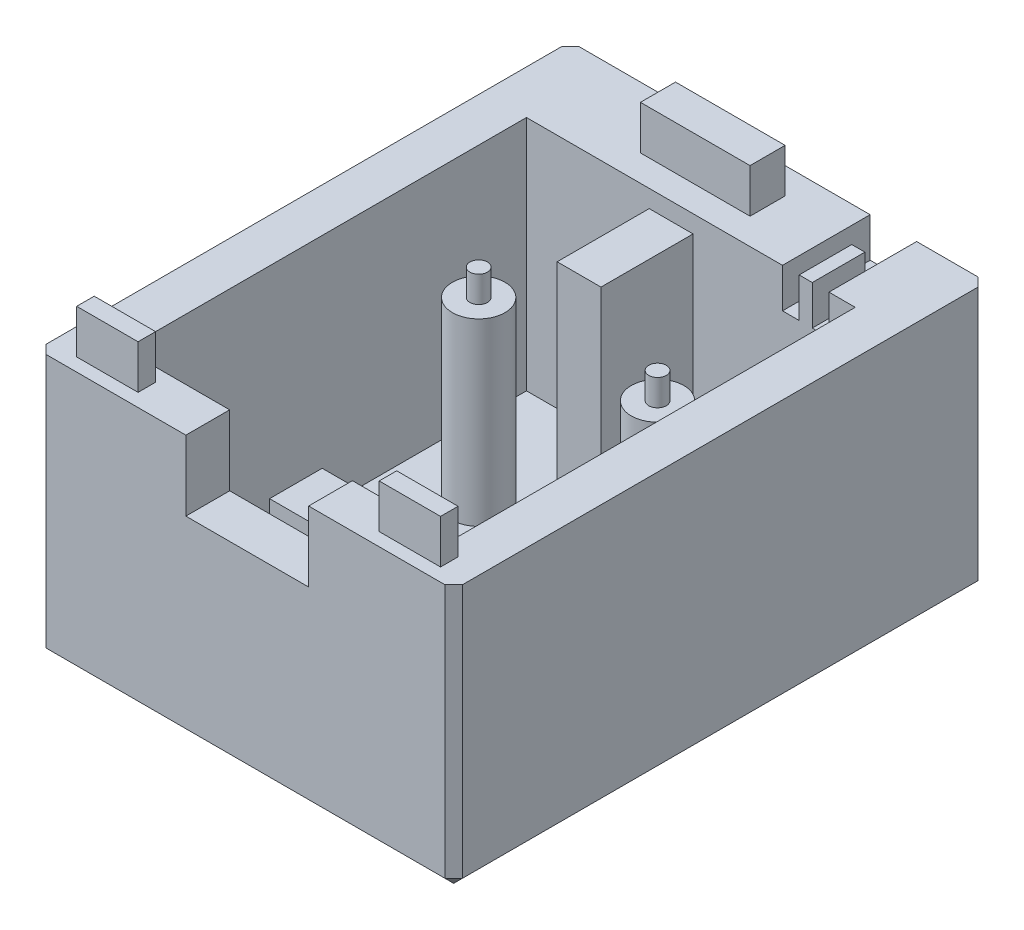
SolidWorks part; units mm, degrees
ref_plane "前视基准面" through (0, 0, 0) normal (0, 0, 1) x (1, 0, 0)
ref_plane "上视基准面" through (0, 0, 0) normal (0, 1, 0) x (1, 0, 0)
ref_plane "右视基准面" through (0, 0, 0) normal (1, 0, 0) x (0, 0, -1)
other "Configuration Table"
sketch "草图1" plane through (0, 0, 0) normal (0, 1, 0) x (1, 0, 0)
  line L1 (-50.0333, 28.8167) -> (-2.5333, 28.8167)
  line L2 (-50.0333, 28.8167) -> (-50.0333, -31.9833)
  line L3 (-50.0333, -31.9833) -> (-2.5333, -31.9833)
  line L4 (-2.5333, 28.8167) -> (-2.5333, -31.9833)
  dimension "D1" = 47.5
  dimension "D2" = 60.8
extrude "凸台-拉伸1" add sketch "草图1" along normal blind 30
sketch "草图3" plane through (0, 30, 0) normal (0, 1, 0) x (1, 0, 0)
  line L0 (-50.0333, 28.8167) -> (-50.0333, -31.9833) construction
  line L1 (-45.0333, 18.8167) -> (-7.5333, 18.8167)
  line L2 (-45.0333, 18.8167) -> (-45.0333, -26.9833)
  line L3 (-45.0333, -26.9833) -> (-7.5333, -26.9833)
  line L4 (-7.5333, 18.8167) -> (-7.5333, -26.9833)
  line L5 (-2.5333, -31.9833) -> (-2.5333, 28.8167) construction
  line L6 (-2.5333, 28.8167) -> (-50.0333, 28.8167) construction
  line L7 (-50.0333, -31.9833) -> (-2.5333, -31.9833) construction
  dimension "D1" = 5
  dimension "D2" = 5
  dimension "D3" = 10
  dimension "D4" = 5
extrude "切除-拉伸1" cut sketch "草图3" against normal blind 27
sketch "草图4" plane through (0, 30, 0) normal (0, 1, 0) x (1, 0, 0)
  line L0 (-45.0333, -26.9833) -> (-7.5333, -26.9833) construction
  line L1 (-33.0833, -26.9833) -> (-19.0833, -26.9833)
  line L2 (-33.0833, -26.9833) -> (-33.0833, -31.9833)
  line L3 (-33.0833, -31.9833) -> (-19.0833, -31.9833)
  line L4 (-19.0833, -26.9833) -> (-19.0833, -31.9833)
  line L5 (-50.0333, -31.9833) -> (-2.5333, -31.9833) construction
  line L6 (-2.5333, -31.9833) -> (-2.5333, 28.8167) construction
  dimension "D1" = 16.55
  dimension "D2" = 14
extrude "切除-拉伸2" cut sketch "草图4" against normal blind 8
sketch "草图5" plane through (0, 3, 0) normal (0, 1, 0) x (1, 0, 0)
  line L0 (-2.5333, -31.9833) -> (-2.5333, 28.8167) construction
  line L2 (-2.5333, 28.8167) -> (-50.0333, 28.8167) construction
  line L3 (-50.0333, 28.8167) -> (-50.0333, -31.9833) construction
  line L4 (-45.0333, -26.9833) -> (-7.5333, -26.9833) construction
  line L5 (-28.5333, -20.9833) -> (-22.5333, -20.9833)
  line L6 (-28.5333, -20.9833) -> (-28.5333, -26.9833)
  line L7 (-28.5333, -26.9833) -> (-22.5333, -26.9833)
  line L8 (-22.5333, -20.9833) -> (-22.5333, -26.9833)
  line L9 (-7.5333, -26.9833) -> (-7.5333, 18.8167) construction
  circle A0 centre (-16.0833, 4.8167) radius 3
  circle A1 centre (-36.4833, 4.8167) radius 3
  point P16 (-25.5333, -20.9833)
  point P19 (-28.5333, -23.9833)
  dimension "D1" = 13.55
  dimension "D3" = 13.55
  dimension "D2" = 24
  dimension "D4" = 24
  dimension "D5" = 6
  dimension "D6" = 15
  dimension "D7" = 6
  dimension "D8" = 31.8
extrude "凸台-拉伸4" add sketch "草图5" along normal blind 20.5
sketch "草图6" plane through (0, 3, 0) normal (0, 1, 0) x (1, 0, 0)
  line L0 (-7.5333, 18.8167) -> (-45.0333, 18.8167) construction
  line L1 (-31.0333, 18.8167) -> (-26.0333, 18.8167)
  line L2 (-31.0333, 18.8167) -> (-31.0333, 8.3167)
  line L3 (-31.0333, 8.3167) -> (-26.0333, 8.3167)
  line L4 (-26.0333, 18.8167) -> (-26.0333, 8.3167)
  line L5 (-45.0333, 18.8167) -> (-45.0333, -26.9833) construction
  circle A1 centre (-36.4833, 4.8167) radius 3
  circle A2 centre (-36.4833, 4.8167) radius 3 construction
  dimension "D1" = 0
  dimension "D2" = 3.5
  dimension "D3" = 5
  dimension "D4" = 0
  dimension "D5" = 14
extrude "凸台-拉伸6" add sketch "草图6" along normal blind 25
sketch "草图7" plane through (0, 23.5, 0) normal (0, 1, 0) x (1, 0, 0)
  circle A0 centre (-36.4833, 4.8167) radius 1
  circle A1 centre (-16.0833, 4.8167) radius 1
extrude "凸台-拉伸7" add sketch "草图7" along normal blind 3
sketch "草图12" plane through (0, 0, -28.8167) normal (0, 0, -1) x (-1, 0, 0)
  line L0 (2.5333, 30) -> (50.0333, 30) construction
  line L1 (10.5333, 30) -> (15.8333, 30)
  line L2 (10.5333, 30) -> (10.5333, 25.5)
  line L3 (10.5333, 25.5) -> (15.8333, 25.5)
  line L4 (15.8333, 30) -> (15.8333, 25.5)
  line L5 (2.5333, 30) -> (2.5333, 0) construction
  dimension "D1" = 8
  dimension "D2" = 5.3
  dimension "D3" = 4.5
extrude "切除-拉伸5" cut sketch "草图12" against normal blind 10
sketch "草图13" plane through (0, 25.5, 0) normal (0, 1, 0) x (1, 0, 0)
  line L0 (-10.5333, 18.8167) -> (-15.8333, 18.8167) construction
  line L1 (-13.9333, 24.8167) -> (-12.4333, 24.8167)
  line L2 (-13.9333, 24.8167) -> (-13.9333, 18.8167)
  line L3 (-13.9333, 18.8167) -> (-12.4333, 18.8167)
  line L4 (-12.4333, 24.8167) -> (-12.4333, 18.8167)
  line L5 (-10.5333, 28.8167) -> (-15.8333, 28.8167) construction
  line L6 (-10.5333, 18.8167) -> (-10.5333, 28.8167) construction
  point P6 (-13.1833, 24.8167)
  dimension "D1" = 4
  dimension "D2" = 1.9
  dimension "D3" = 1.5
extrude "凸台-拉伸8" add sketch "草图13" along normal blind 4.5
sketch "草图14" plane through (0, 3, 0) normal (0, 1, 0) x (1, 0, 0)
  line L0 (-45.0333, 18.8167) -> (-45.0333, -26.9833) construction
  line L1 (-41.0333, -0.5904) -> (-11.0333, -0.5904)
  line L2 (-41.0333, -0.5904) -> (-41.0333, -3.5904)
  line L3 (-41.0333, -3.5904) -> (-11.0333, -3.5904)
  line L4 (-11.0333, -0.5904) -> (-11.0333, -3.5904)
  line L5 (-41.0333, -6.5904) -> (-41.0333, -9.5904)
  line L6 (-41.0333, -6.5904) -> (-11.0333, -6.5904)
  line L7 (-11.0333, -6.5904) -> (-11.0333, -9.5904)
  line L8 (-41.0333, -9.5904) -> (-11.0333, -9.5904)
  line L9 (-41.0333, -12.5904) -> (-41.0333, -15.5904)
  line L10 (-41.0333, -12.5904) -> (-11.0333, -12.5904)
  line L11 (-11.0333, -12.5904) -> (-11.0333, -15.5904)
  line L12 (-41.0333, -15.5904) -> (-11.0333, -15.5904)
  point P4 (-41.0333, -2.0904)
  dimension "D1" = 3
  dimension "D2" = 30
  dimension "D3" = 4
  dimension "D4" = 3
extrude "切除-拉伸6" cut sketch "草图14" against normal blind 3
chamfer "倒角1" distance 1 angle 45 8 edges at (-2.5333, 15, 31.9833) (-26.2833, 0, 31.9833) (-50.0333, 15, 31.9833) (-50.0333, 0, 1.5833) (-50.0333, 15, -28.8167) (-2.5333, 0, 1.5833) (-26.2833, 0, -28.8167) (-2.5333, 15, -28.8167)
sketch "草图16" plane through (0, 30, 0) normal (0, 1, 0) x (1, 0, 0)
  line L0 (-15.8333, 28.8167) -> (-49.0333, 28.8167) construction
  line L1 (-35.0333, 25.8167) -> (-22.5333, 25.8167)
  line L2 (-35.0333, 25.8167) -> (-35.0333, 21.8167)
  line L3 (-35.0333, 21.8167) -> (-22.5333, 21.8167)
  line L4 (-22.5333, 25.8167) -> (-22.5333, 21.8167)
  line L5 (-50.0333, 27.8167) -> (-50.0333, -30.9833) construction
  line L6 (-2.5333, -30.9833) -> (-2.5333, 27.8167) construction
  line L7 (-19.0833, -31.9833) -> (-3.5333, -31.9833) construction
  line L8 (-12.5333, -28.4833) -> (-5.5333, -28.4833)
  line L9 (-12.5333, -28.4833) -> (-12.5333, -30.4833)
  line L10 (-12.5333, -30.4833) -> (-5.5333, -30.4833)
  line L11 (-5.5333, -28.4833) -> (-5.5333, -30.4833)
  line L12 (-47.0333, -28.4833) -> (-40.0333, -28.4833)
  line L13 (-47.0333, -28.4833) -> (-47.0333, -30.4833)
  line L14 (-47.0333, -30.4833) -> (-40.0333, -30.4833)
  line L15 (-40.0333, -28.4833) -> (-40.0333, -30.4833)
  line L16 (-49.0333, -31.9833) -> (-33.0833, -31.9833) construction
  dimension "D1" = 4
  dimension "D2" = 3
  dimension "D3" = 15
  dimension "D4" = 20
  dimension "D5" = 7
  dimension "D6" = 2
  dimension "D7" = 1.5
  dimension "D8" = 3
  dimension "D9" = 2
  dimension "D10" = 7
  dimension "D11" = 3
  dimension "D12" = 1.5
extrude "凸台-拉伸9" add sketch "草图16" along normal blind 5
